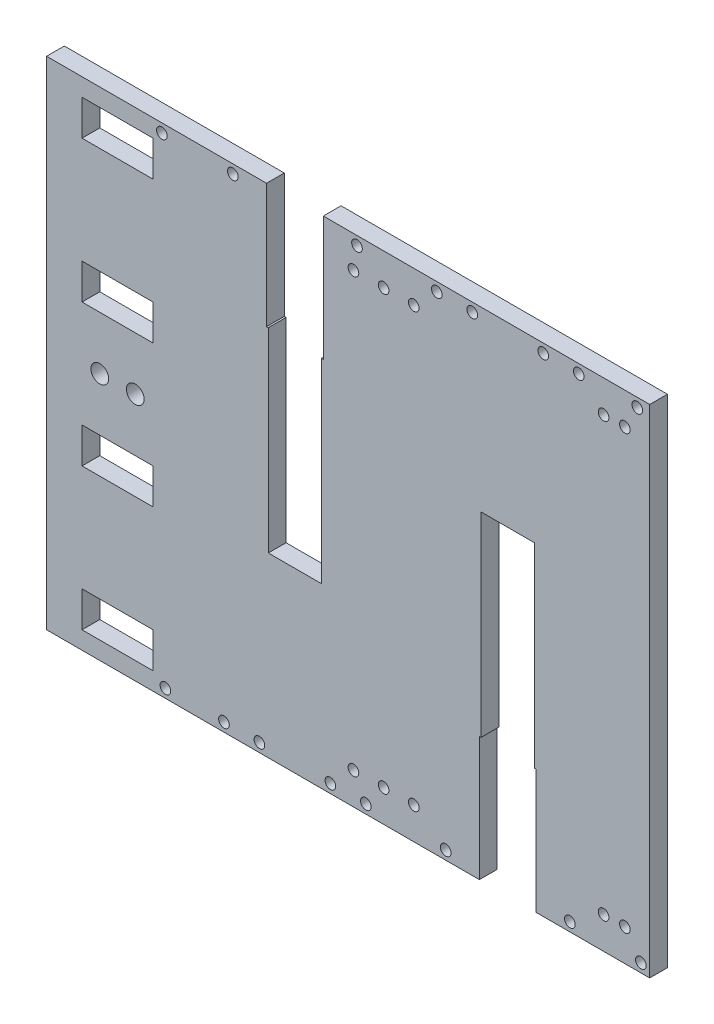
SolidWorks part; units mm, degrees
ref_plane "정면" through (0, 0, 0) normal (0, 0, 1) x (1, 0, 0)
ref_plane "윗면" through (0, 0, 0) normal (0, 1, 0) x (1, 0, 0)
ref_plane "우측면" through (0, 0, 0) normal (1, 0, 0) x (0, 0, -1)
sketch "스케치1" plane through (0, 0, 0) normal (0, 0, 1) x (1, 0, 0)
  line L1 (-70, 70) -> (70, 70)
  line L2 (-70, 70) -> (-70, -70)
  line L3 (-70, -70) -> (70, -70)
  line L4 (70, 70) -> (70, -70)
  line L5 (-70, 70) -> (70, -70) construction
  line L6 (-70, -70) -> (70, 70) construction
  point P0 (0, 0)
  dimension "D1" = 140
  dimension "D2" = 140
extrude "보스-돌출1" add sketch "스케치1" along normal blind 5
sketch "스케치2" plane through (0, 0, 5) normal (0, 0, 1) x (1, 0, 0)
  line L0 (70, 70) -> (-70, 70) construction
  line L1 (-38, 70) -> (-22, 70)
  line L2 (-38, 70) -> (-38, 35)
  line L3 (-37.5, -20) -> (-22.5, -20)
  line L4 (-22, 70) -> (-22, 35)
  line L5 (0, 70) -> (0, -70)
  line L6 (-70, -70) -> (70, -70) construction
  line L7 (-70, -70) -> (70, -70) construction
  line L8 (-70, 70) -> (-70, -70) construction
  line L9 (70, 70) -> (-70, -70) construction
  line L10 (22, -70) -> (22, -35)
  line L11 (38, -70) -> (38, -35)
  line L12 (38, -35) -> (37.5, -35)
  line L13 (38, 70) -> (22, 70)
  line L14 (70, 0) -> (-70, 0) construction
  line L15 (70, -70) -> (70, 70) construction
  line L16 (22, -35) -> (22.5, -35)
  line L17 (22.5, -35) -> (22.5, 20)
  line L18 (38, -70) -> (22, -70)
  line L19 (37.5, -35) -> (37.5, 20)
  line L20 (22.5, 20) -> (37.5, 20)
  line L21 (-38, 35) -> (-37.5, 35)
  line L22 (-22, 35) -> (-22.5, 35)
  line L23 (-37.5, 35) -> (-37.5, -20)
  line L24 (-22.5, 35) -> (-22.5, -20)
sketch "스케치3" plane through (0, 0, 5) normal (0, 0, 1) x (1, 0, 0)
  line L0 (-70, -70) -> (70, -70) construction
  line L1 (-70, 70) -> (-100, 70)
  line L2 (-70, 70) -> (-70, -70)
  line L3 (-70, -70) -> (-100, -70)
  line L4 (-100, 70) -> (-100, -70)
  dimension "D1" = 30
extrude "보스-돌출2" add sketch "스케치3" against normal blind 5
sketch "스케치4" plane through (0, 0, 0) normal (0, 0, -1) x (-1, 0, 0)
  line L0 (-70, 0) -> (100, 0)
  line L1 (-70, -70) -> (-70, 70) construction
  line L2 (100, 70) -> (100, -70) construction
  line L3 (100, 0) -> (100, 70)
  line L4 (100, 0) -> (100, -70)
  line L5 (90, 70) -> (90, -70)
  line L6 (-70, 70) -> (100, 70) construction
  line L7 (100, -70) -> (-70, -70) construction
  line L8 (90, 65) -> (90, 55)
  line L9 (90, 65) -> (70, 65)
  line L10 (90, 55) -> (70, 55)
  line L11 (70, 65) -> (70, 55)
  line L12 (90, 25) -> (90, 15)
  line L13 (90, 25) -> (70, 25)
  line L14 (90, 15) -> (70, 15)
  line L15 (70, 25) -> (70, 15)
  line L16 (90, -15) -> (70, -15)
  line L17 (70, -25) -> (70, -15)
  line L18 (90, -25) -> (70, -25)
  line L19 (90, -55) -> (70, -55)
  line L20 (70, -65) -> (70, -55)
  line L21 (90, -65) -> (70, -65)
  dimension "D1" = 10
  dimension "D2" = 10
  dimension "D3" = 20
  dimension "D4" = 5
  dimension "D5" = 20
  dimension "D6" = 10
  dimension "D7" = 45
extrude "컷-돌출9" cut sketch "스케치2" against normal blind 10 contours L23 L3 L24 L22 L4 L1 L2 L21 | L17 L20 L19 L12 L11 L18 L10 L16
extrude "컷-돌출2" cut sketch "스케치4" against normal blind 10 contours L9 L11 L10 L5 | L13 L15 L14 L5 | L18 L5 L16 L17 | L21 L5 L19 L20
sketch "스케치5" plane through (0, 0, 5) normal (0, 0, 1) x (1, 0, 0)
  line L0 (-100, 67.5) -> (70, 67.5)
  line L1 (-100, 70) -> (-100, -70) construction
  line L2 (70, -70) -> (70, 70) construction
  line L3 (70, 70) -> (-22, 70) construction
  line L4 (-70, -70) -> (70, 70)
  line L5 (-70, 70) -> (-70, -70)
  line L6 (-38, 70) -> (-100, 70) construction
  line L7 (-100, -70) -> (22, -70) construction
  line L8 (70, -70) -> (-70, 70)
  line L9 (67.5, -67.5) -> (47.5, -67.5)
  line L10 (38, -70) -> (70, -70) construction
  circle A0 centre (66.5, 67.5) radius 1.5
  circle A1 centre (50, 67.5) radius 1.5
  circle A2 centre (10, 67.5) radius 1.5
  circle A3 centre (40, 67.5) radius 1.5
  circle A4 centre (20, 67.5) radius 1.5
  circle A5 centre (-47.5, 67.5) radius 1.5
  circle A6 centre (-12.5, 67.5) radius 1.5
  circle A7 centre (-67.5, 67.5) radius 1.5
  circle A8 centre (0, 0) radius 2.5
  circle A9 centre (-66.5, -67.5) radius 1.5
  circle A10 centre (-50, -67.5) radius 1.5
  circle A11 centre (-10, -67.5) radius 1.5
  circle A12 centre (-40, -67.5) radius 1.5
  circle A13 centre (-20, -67.5) radius 1.5
  circle A14 centre (47.5, -67.5) radius 1.5
  circle A15 centre (12.5, -67.5) radius 1.5
  circle A16 centre (67.5, -67.5) radius 1.5
  point P55 (0, 0)
  dimension "D2" = 3
  dimension "D4" = 16.5
  dimension "D5" = 10
  dimension "D6" = 20
  dimension "D7" = 10
  dimension "D8" = 35
  dimension "D9" = 22.5
  dimension "D10" = 20
  dimension "D11" = 30
  dimension "D12" = 5
  dimension "D14" = 135
  dimension "D1" = 2.5
  dimension "D3" = 3.5
  dimension "D13" = 2
sketch "스케치6" plane through (0, 0, 5) normal (0, 0, 1) x (1, 0, 0)
  line L0 (70, 70) -> (70, 65)
  line L1 (70, -70) -> (70, 70) construction
  line L2 (70, 65) -> (-100, 65) construction
  line L3 (-100, 70) -> (-100, -70) construction
  circle A0 centre (-66.5, -67.5) radius 1.5
  circle A1 centre (-50, -67.5) radius 1.5
  circle A2 centre (-40, -67.5) radius 1.5
  circle A3 centre (-20, -67.5) radius 1.5
  circle A4 centre (-10, -67.5) radius 1.5
  circle A5 centre (12.5, -67.5) radius 1.5
  circle A6 centre (47.5, -67.5) radius 1.5
  circle A7 centre (67.5, -67.5) radius 1.5
  circle A8 centre (-67.5, 67.5) radius 1.5
  circle A9 centre (-47.5, 67.5) radius 1.5
  circle A10 centre (-12.5, 67.5) radius 1.5
  circle A11 centre (10, 67.5) radius 1.5
  circle A12 centre (20, 67.5) radius 1.5
  circle A13 centre (40, 67.5) radius 1.5
  circle A14 centre (50, 67.5) radius 1.5
  circle A15 centre (66.5, 67.5) radius 1.5
  dimension "D1" = 3
  dimension "D2" = 3
  dimension "D3" = 3
  dimension "D4" = 3
  dimension "D5" = 3
  dimension "D6" = 3
  dimension "D7" = 3
  dimension "D8" = 3
  dimension "D9" = 3
  dimension "D10" = 3
  dimension "D11" = 3
  dimension "D12" = 3
  dimension "D13" = 3
  dimension "D14" = 3
  dimension "D15" = 3
  dimension "D16" = 3
extrude "컷-돌출6" cut sketch "스케치6" against normal blind 31 contours A4 | A3 | A0 | A8 | A9 | A10 | A11 | A12 | A13 | A15 | A7 | A6 | A5 | A2 | A1 | A14
sketch "스케치7" plane through (0, 0, 5) normal (0, 0, 1) x (1, 0, 0)
  line L0 (-100, 0) -> (70, 0)
  line L1 (-100, 70) -> (-100, -70) construction
  line L2 (70, -70) -> (70, 70) construction
  circle A0 centre (-85, 0) radius 2.5
  circle A1 centre (-75, 0) radius 2.5
  dimension "D1" = 5
  dimension "D2" = 5
extrude "컷-돌출7" cut sketch "스케치7" against normal blind 10 contours L0 A0 | L0 A0 | L0 A1 | L0 A1
sketch "스케치8" plane through (0, 0, 0) normal (0, 0, -1) x (-1, 0, 0)
  line L0 (100, 61) -> (-70, 61)
  line L1 (100, 70) -> (100, -70) construction
  line L2 (-70, -70) -> (-70, 70) construction
  line L4 (100, 0) -> (-70, 0)
  line L5 (38, 70) -> (100, 70) construction
  line L6 (-70, -70) -> (-70, 70) construction
  circle A0 centre (-63, 61) radius 1.5
  circle A1 centre (-3.5, 61) radius 1.5
  circle A2 centre (-57, 61) radius 1.5
  circle A3 centre (13.5, 61) radius 1.5
  circle A4 centre (5, 61) radius 1.5
  circle A5 centre (5, -61) radius 1.5
  circle A6 centre (13.5, -61) radius 1.5
  circle A7 centre (-57, -61) radius 1.5
  circle A8 centre (-3.5, -61) radius 1.5
  circle A9 centre (-63, -61) radius 1.5
  dimension "D1" = 9
  dimension "D2" = 3
  dimension "D3" = 66.5
  dimension "D4" = 7
  dimension "D6" = 75
  dimension "D7" = 83.5
  dimension "D5" = 13
extrude "컷-돌출8" cut sketch "스케치8" against normal blind 10 contours L0 A2 | L0 A2 | L0 A1 | L0 A1 | L0 A0 | L0 A0 | A6 | A5 | L0 A3 | L0 A3 | L0 A4 | L0 A4 | A8 | A9 | A7
